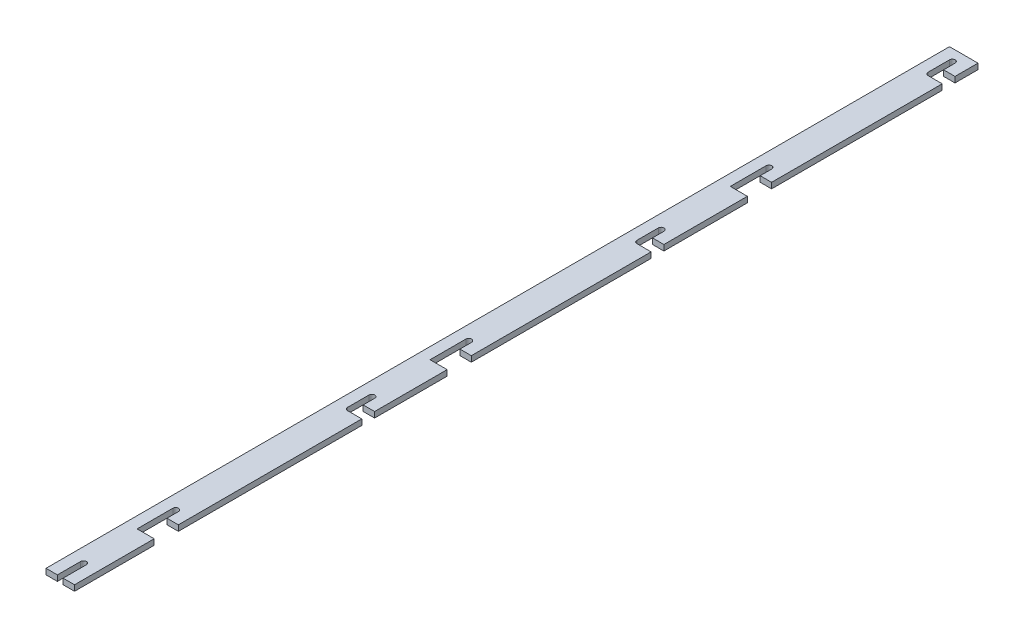
SolidWorks part; units mm, degrees
ref_plane "Front Plane" through (0, 0, 0) normal (0, 0, 1) x (1, 0, 0)
ref_plane "Top Plane" through (0, 0, 0) normal (0, 1, 0) x (1, 0, 0)
ref_plane "Right Plane" through (0, 0, 0) normal (1, 0, 0) x (0, 0, -1)
sketch "Sketch1" plane through (0, 0, 0) normal (0, 1, 0) x (1, 0, 0)
  line L1 (0, 0) -> (7.9375, 0)
  line L2 (0, 0) -> (0, 251.46)
  line L3 (0, 251.46) -> (7.9375, 251.46)
  line L4 (7.9375, 0) -> (7.9375, 251.46)
extrude "Boss-Extrude1" add sketch "Sketch1" along normal blind 1.5875
sketch "Sketch2" plane through (0, 1.5875, 0) normal (0, 1, 0) x (1, 0, 0)
  line L0 (7.9375, 245.0592) -> (4.7625, 245.0592)
  line L1 (7.9375, 0) -> (7.9375, 251.46) construction
  line L2 (4.7625, 245.0592) -> (4.7625, 248.285)
  line L3 (7.9375, 194.0052) -> (4.7625, 194.0052)
  line L4 (3.175, 248.285) -> (3.175, 242.297)
  line L5 (3.9688, 241.5032) -> (7.9375, 241.5032)
  line L6 (7.9375, 241.5032) -> (7.9375, 245.0592)
  line L7 (3.9688, 251.46) -> (3.9688, -8.4025) construction
  line L8 (7.9375, 251.46) -> (0, 251.46) construction
  line L9 (4.7625, 194.0052) -> (4.7625, 197.231)
  line L10 (3.175, 197.231) -> (3.175, 191.243)
  line L11 (7.9375, 103.7082) -> (3.175, 103.7082)
  line L12 (7.9375, 190.4492) -> (7.9375, 194.0052)
  line L13 (7.9375, 160.4772) -> (7.9375, 164.0332)
  line L14 (7.9375, 164.0332) -> (4.7625, 164.0332)
  line L15 (4.7625, 164.0332) -> (4.7625, 167.259)
  line L16 (3.175, 167.259) -> (3.175, 161.271)
  line L17 (3.9688, 160.4772) -> (7.9375, 160.4772)
  line L18 (7.9375, 106.8832) -> (7.9375, 110.4392)
  line L19 (7.9375, 110.4392) -> (4.7625, 110.4392)
  line L20 (4.7625, 110.4392) -> (4.7625, 113.665)
  line L21 (3.175, 113.665) -> (3.175, 107.677)
  line L22 (7.9375, 22.1742) -> (3.175, 22.1742)
  line L23 (7.9375, 83.5152) -> (4.7625, 83.5152)
  line L24 (7.9375, 79.9592) -> (7.9375, 83.5152)
  line L25 (3.9688, 79.9592) -> (7.9375, 79.9592)
  line L26 (3.175, 86.741) -> (3.175, 80.753)
  line L27 (4.7625, 83.5152) -> (4.7625, 86.741)
  line L28 (7.9375, 25.3492) -> (7.9375, 28.9052)
  line L29 (7.9375, 28.9052) -> (4.7625, 28.9052)
  line L30 (4.7625, 28.9052) -> (4.7625, 32.131)
  line L31 (3.175, 32.131) -> (3.175, 26.143)
  line L32 (3.175, 6.477) -> (3.175, -0.9074)
  line L33 (3.175, 191.243) -> (3.175, 187.2742)
  line L34 (3.175, 187.2742) -> (7.9375, 187.2742)
  line L35 (7.9375, 187.2742) -> (7.9375, 190.4492)
  line L36 (3.175, 103.7082) -> (3.175, 107.677)
  line L37 (3.9688, 190.4492) -> (7.9375, 190.4492) [skipped]
  line L38 (3.9688, 190.4492) -> (7.9375, 190.4492) [skipped]
  line L39 (7.9375, 106.8832) -> (7.9375, 103.7082)
  line L40 (3.175, 22.1742) -> (3.175, 26.143)
  line L41 (3.9688, 106.8832) -> (7.9375, 106.8832) [skipped]
  line L42 (3.9688, 106.8832) -> (7.9375, 106.8832) [skipped]
  line L43 (7.9375, 25.3492) -> (7.9375, 22.1742)
  line L44 (3.175, -0.9074) -> (4.7625, -0.9074)
  line L45 (3.9688, 25.3492) -> (7.9375, 25.3492) [skipped]
  line L46 (4.7625, -0.9074) -> (4.7625, 6.477)
  arc A0 (4.7625, 248.285) -> (3.175, 248.285) centre (3.9688, 248.285) ccw
  arc A1 (3.9688, 241.5032) -> (3.175, 242.297) centre (3.9688, 242.297) cw
  arc A2 (4.7625, 197.231) -> (3.175, 197.231) centre (3.9688, 197.231) ccw
  arc A3 (4.7625, 6.477) -> (3.175, 6.477) centre (3.9688, 6.477) ccw
  arc A4 (4.7625, 167.259) -> (3.175, 167.259) centre (3.9688, 167.259) ccw
  arc A5 (3.9688, 160.4772) -> (3.175, 161.271) centre (3.9688, 161.2709) cw
  arc A6 (4.7625, 113.665) -> (3.175, 113.665) centre (3.9688, 113.665) ccw
  arc A8 (3.9688, 79.9592) -> (3.175, 80.753) centre (3.9688, 80.7529) cw
  arc A9 (4.7625, 86.741) -> (3.175, 86.741) centre (3.9688, 86.741) ccw
  arc A10 (4.7625, 32.131) -> (3.175, 32.131) centre (3.9688, 32.131) ccw
  arc A12 (3.9688, 190.4492) -> (3.175, 191.243) centre (3.9688, 191.243) cw [skipped]
  arc A13 (3.9688, 190.4492) -> (3.175, 191.243) centre (3.9687, 191.243) cw [skipped]
  arc A14 (3.9688, 106.8832) -> (3.175, 107.677) centre (3.9688, 107.6769) cw [skipped]
  arc A15 (3.9688, 106.8832) -> (3.175, 107.677) centre (3.9688, 107.6769) cw [skipped]
  arc A16 (3.9688, 25.3492) -> (3.175, 26.143) centre (3.9688, 26.1429) cw [skipped]
extrude "Cut-Extrude1" cut sketch "Sketch2" against normal blind 1.5875
